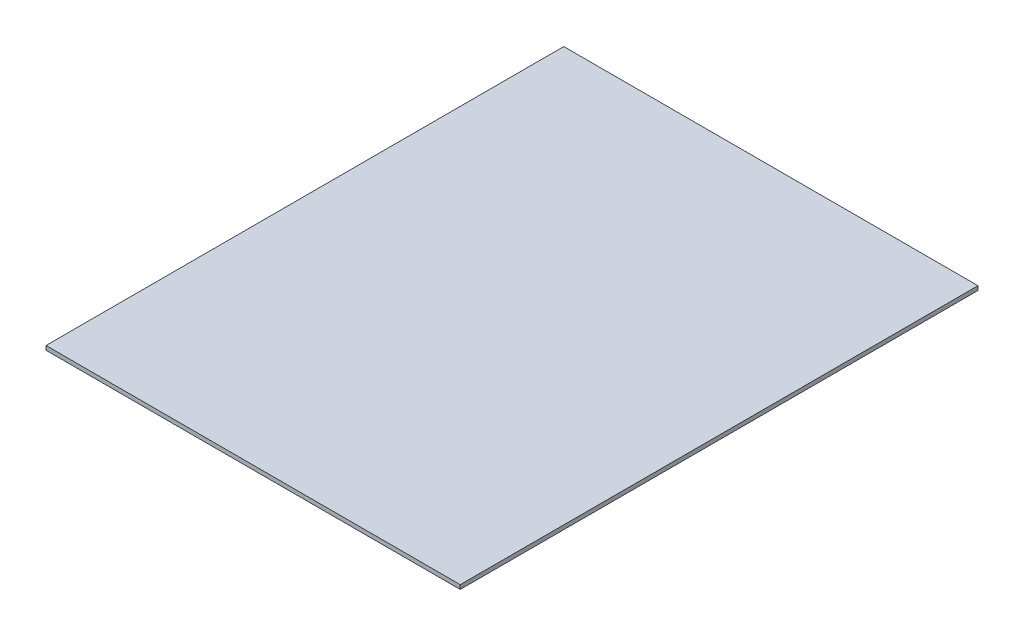
SolidWorks part; units mm, degrees
ref_plane "Front Plane" through (0, 0, 0) normal (0, 0, 1) x (1, 0, 0)
ref_plane "Top Plane" through (0, 0, 0) normal (0, 1, 0) x (1, 0, 0)
ref_plane "Right Plane" through (0, 0, 0) normal (1, 0, 0) x (0, 0, -1)
other "Configuration Table"
sketch "Sketch1" plane through (0, 0, 0) normal (0, 0, 1) x (1, 0, 0)
  line L1 (150, 1166) -> (550, 1166)
  line L2 (150, 1166) -> (150, 1170)
  line L3 (150, 1170) -> (550, 1170)
  line L4 (550, 1166) -> (550, 1170)
extrude "OVEN_OMAKE_hazne_1_tepsi_duzlemi_117_1" add sketch "Sketch1" against normal blind 500 from offset 60 separate body
